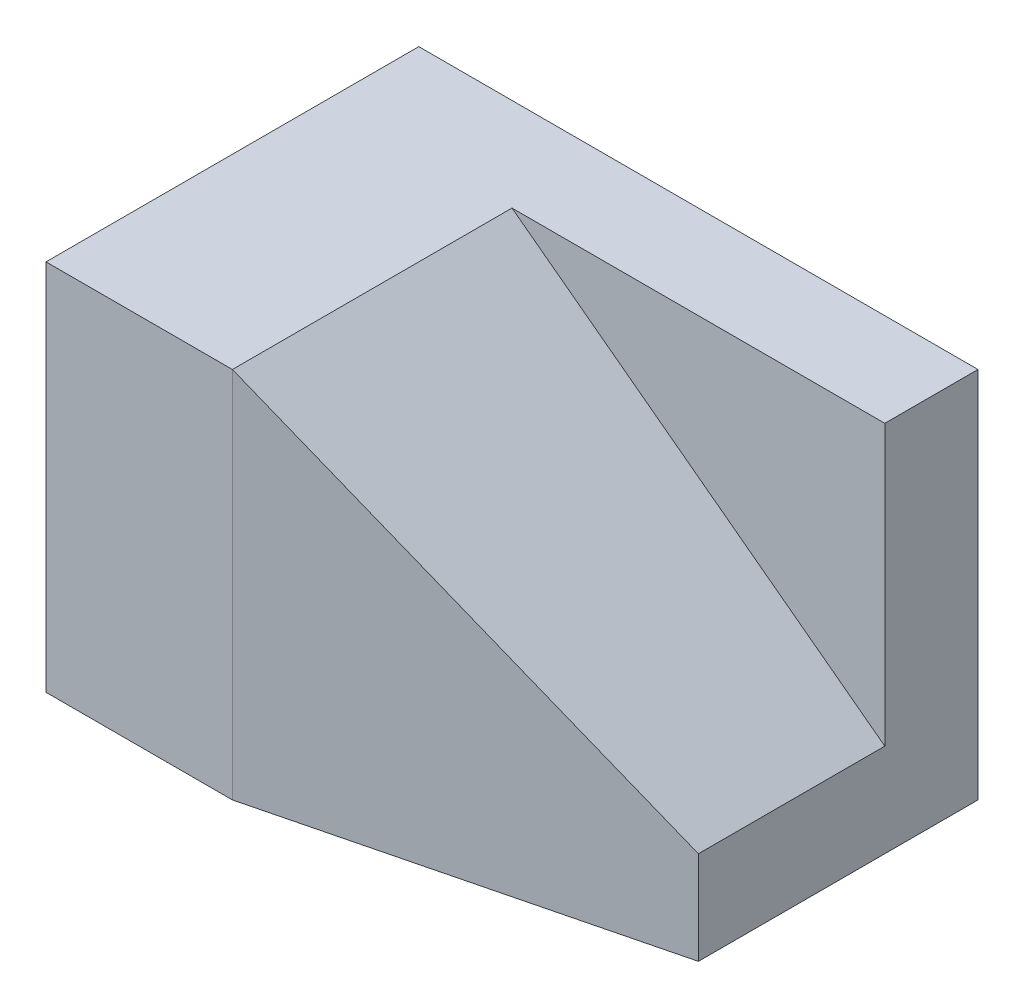
SolidWorks part; units mm, degrees
ref_plane "前基準面" through (0, 0, 0) normal (0, 0, 1) x (1, 0, 0)
ref_plane "上基準面" through (0, 0, 0) normal (0, 1, 0) x (1, 0, 0)
ref_plane "右基準面" through (0, 0, 0) normal (1, 0, 0) x (0, 0, -1)
sketch "草圖1" plane through (0, 0, 0) normal (0, 1, 0) x (1, 0, 0)
  line L1 (0, 0) -> (10, 0)
  line L2 (0, 0) -> (0, 20)
  line L3 (0, 20) -> (10, 20)
  line L4 (10, 0) -> (10, 20)
  line L5 (0, 20) -> (30, 20)
  line L6 (0, 20) -> (0, 15)
  line L7 (0, 15) -> (30, 15)
  line L8 (30, 20) -> (30, 15)
  dimension "D1" = 5
  dimension "D2" = 10
  dimension "D3" = 20
  dimension "D4" = 30
extrude "填料-伸長1" add sketch "草圖1" along normal blind 20 contours L7 L2 L1 L4 | L2 L7 L4 L3 | L8 L5 L4 L7
sketch "草圖3" plane through (30, 0, 0) normal (1, 0, 0) x (0, 0, -1)
  line L0 (15, 20) -> (15, 0) construction
  line L1 (5, 0) -> (15, 0)
  line L2 (5, 5) -> (5, 0)
  line L3 (5, 5) -> (15, 5)
  line L4 (15, 0) -> (15, 5)
  line L5 (0, 20) -> (0, 0) construction
  line L8 (0, 0) -> (15, 0) construction
  point P9 (15, 5.9178)
  dimension "D1" = 5
  dimension "D2" = 5
sketch "草圖4" plane through (10, 0, 0) normal (1, 0, 0) x (0, 0, -1)
  line L4 (0, 0) -> (15, 0)
  line L5 (15, 0) -> (15, 20)
  line L6 (15, 20) -> (0, 20)
  line L7 (0, 20) -> (0, 0)
  line L8 (0, 0) -> (15, 0)
  line L9 (15, 0) -> (15, 20)
  line L10 (15, 20) -> (0, 20)
  line L11 (0, 20) -> (0, 0)
  dimension "D1" = 0
loft "疊層拉伸1" add profiles "草圖4", "草圖3"
